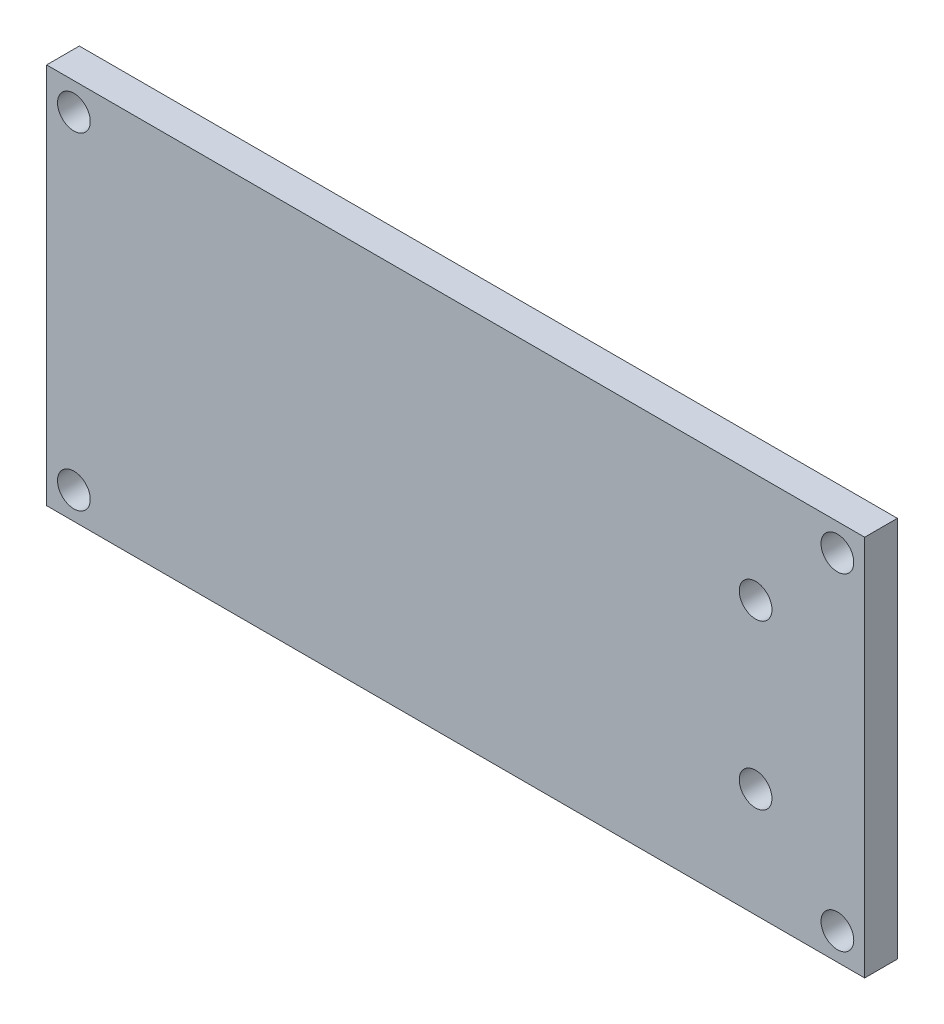
SolidWorks part; units mm, degrees
material "ABS"
ref_plane "Front Plane" through (0, 0, 0) normal (0, 0, 1) x (1, 0, 0)
ref_plane "Top Plane" through (0, 0, 0) normal (0, 1, 0) x (1, 0, 0)
ref_plane "Right Plane" through (0, 0, 0) normal (1, 0, 0) x (0, 0, -1)
sketch "Sketch1" plane through (0, 0, 0) normal (0, 0, 1) x (1, 0, 0)
  line L5 (0, 0) -> (75, 0)
  line L6 (0, 0) -> (0, 35)
  line L7 (0, 35) -> (75, 35)
  line L8 (75, 0) -> (75, 35)
  circle A0 centre (2.5, 32.5) radius 1.5
  circle A1 centre (2.5, 2.5) radius 1.5
  circle A2 centre (72.5, 2.5) radius 1.5
  circle A3 centre (72.5, 32.5) radius 1.5
  circle A4 centre (65, 10) radius 1.5
  circle A5 centre (65, 25) radius 1.5
  point P16 (0, 0)
  dimension "D1" = 3
  dimension "D3" = 75
  dimension "D4" = 2.5
  dimension "D5" = 2.5
  dimension "D6" = 2.5
  dimension "D7" = 2.5
  dimension "D8" = 3
  dimension "D9" = 10
  dimension "D10" = 10
  dimension "D11" = 10
  dimension "D2" = 35
extrude "Boss-Extrude1" add sketch "Sketch1" along normal blind 3
